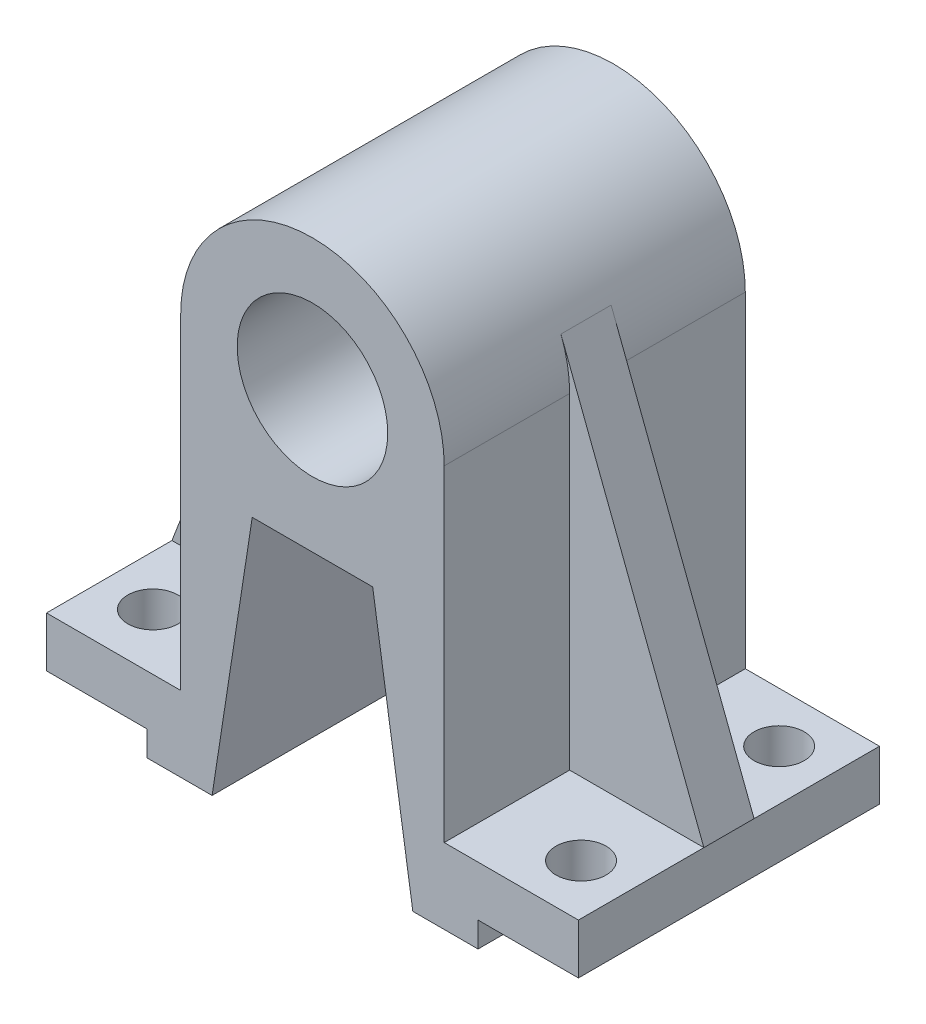
SolidWorks part; units mm, degrees
ref_plane "Front Plane" through (0, 0, 0) normal (0, 0, 1) x (1, 0, 0)
ref_plane "Top Plane" through (0, 0, 0) normal (0, 1, 0) x (1, 0, 0)
ref_plane "Right Plane" through (0, 0, 0) normal (1, 0, 0) x (0, 0, -1)
sketch "Sketch2" plane through (0, 0, 0) normal (0, 0, 1) x (1, 0, 0)
  line L0 (-27.7507, 4.7495) -> (-27.7507, -60.2505)
  line L1 (24.7552, 4.7495) -> (24.7552, -60.2505)
  line L2 (24.7552, -60.2505) -> (51.5022, -60.2505)
  line L3 (51.5022, -60.2505) -> (51.5022, -70.2505)
  line L4 (51.5022, -70.2505) -> (31.5022, -70.2505)
  line L5 (31.5022, -70.2505) -> (31.5022, -75.2505)
  line L6 (31.5022, -75.2505) -> (18.5022, -75.2505)
  line L7 (18.5022, -75.2505) -> (10.5022, -23.2505)
  line L8 (10.5022, -23.2505) -> (-13.4978, -23.2505)
  line L9 (-13.4978, -23.2505) -> (-21.4978, -75.2505)
  line L10 (-21.4978, -75.2505) -> (-34.4978, -75.2505)
  line L11 (-34.4978, -75.2505) -> (-34.4978, -70.2505)
  line L12 (-34.4978, -70.2505) -> (-54.4978, -70.2505)
  line L13 (-54.4978, -70.2505) -> (-54.4978, -60.2505)
  line L14 (-54.4978, -60.2505) -> (-27.7507, -60.2505)
  line L15 (-1.4978, 31.0025) -> (-1.4978, -21.5034) construction
  line L16 (-27.7507, 4.7495) -> (24.7552, 4.7495)
  circle A0 centre (-1.4978, 4.7495) radius 26.2529
  point P20 (-1.4978, -23.2505)
  dimension "D1" = 40
  dimension "D2" = 66
  dimension "D3" = 106
  dimension "D4" = 24
  dimension "D5" = 10
  dimension "D6" = 28
  dimension "D7" = 75
  dimension "D8" = 5
extrude "Boss-Extrude1" add sketch "Sketch2" against normal blind 60 contours L15 A0 L16 | A0 L15 L16 | A0 L0 L14 L13 L12 L11 L10 L9 L8 L7 L6 L5 L4 L3 L2 L1
sketch "Sketch3" plane through (0, 0, 0) normal (0, 0, 1) x (1, 0, 0)
  circle A0 centre (-1.4978, 4.7495) radius 15
extrude "Cut-Extrude1" cut sketch "Sketch3" against normal blind 60
sketch "Sketch4" plane through (0, -60.2505, 0) normal (0, 1, 0) x (1, 0, 0)
  line L0 (51.5022, 60) -> (51.5022, 0) construction
  line L1 (24.7552, 60) -> (51.5022, 60) construction
  line L2 (-54.4978, 60) -> (-54.4978, 0) construction
  line L3 (-54.4978, 60) -> (-27.7507, 60) construction
  circle A0 centre (41.5022, 10.5242) radius 5
  circle A1 centre (41.5022, 50) radius 5
  circle A2 centre (-44.4978, 50) radius 5
  circle A3 centre (-44.4978, 11.2095) radius 5
  point P12 (-29.1409, 75.8625)
  point P13 (0, 0)
  point P18 (0, 0)
  dimension "D1" = 10
  dimension "D2" = 10
  dimension "D3" = 10
  dimension "D4" = 10
extrude "Cut-Extrude2" cut sketch "Sketch4" against normal blind 60
move or copy body "Body-Move/Copy1" bodies to move or copy 104 copy no translate (0, 0, 30) parameters "D1"=0, "D2"=0, "D3"=30
sketch "Sketch5" plane through (0, 0, 0) normal (0, 0, 1) x (1, 0, 0)
  line L0 (23.0194, 14.1371) -> (51.5022, -60.2505)
  line L1 (51.5022, -60.2505) -> (24.7552, -60.2505)
  line L2 (23.0194, 14.1371) -> (23.0194, -60.2505)
  line L3 (23.0194, -60.2505) -> (24.7552, -60.2505)
  arc A0 (24.7552, 4.7495) -> (-27.7507, 4.7495) centre (-1.4978, 4.7495) ccw construction
extrude "Boss-Extrude2" add sketch "Sketch5" along normal mid plane 10
sketch "Sketch7" plane through (0, 0, 0) normal (0, 0, 1) x (1, 0, 0)
  line L0 (-54.4978, -60.2505) -> (-26.889, 11.4206)
  line L1 (-26.889, 11.4206) -> (-26.889, -60.2505)
  line L2 (-26.889, -60.2505) -> (-54.4978, -60.2505)
  arc A0 (24.7552, 4.7495) -> (-27.7507, 4.7495) centre (-1.4978, 4.7495) ccw construction
extrude "Boss-Extrude3" add sketch "Sketch7" along normal mid plane 10
